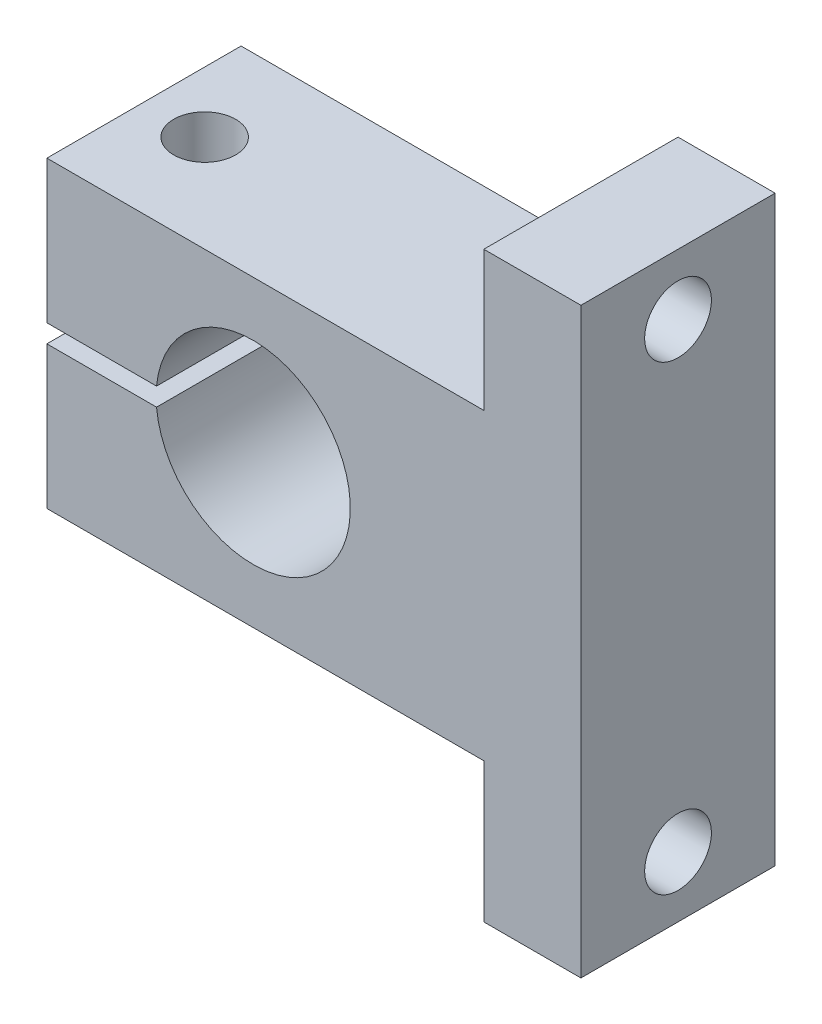
SolidWorks part; units mm, degrees
material "Liga 6061"
ref_plane "Plano frontal" through (0, 0, 0) normal (0, 0, 1) x (1, 0, 0)
ref_plane "Plano superior" through (0, 0, 0) normal (0, 1, 0) x (1, 0, 0)
ref_plane "Plano direito" through (0, 0, 0) normal (1, 0, 0) x (0, 0, -1)
sketch "Esboço1" plane through (0, 0, 0) normal (0, 0, 1) x (1, 0, 0)
  line L0 (0, 0) -> (0, 48)
  line L1 (0, 48) -> (-8, 48)
  line L2 (-8, 48) -> (-8, 36.5)
  line L3 (-8, 36.5) -> (-44, 36.5)
  line L4 (-44, 36.5) -> (-44, 24.75)
  line L5 (-44, 11.5) -> (-8, 11.5)
  line L6 (-8, 11.5) -> (-8, 0)
  line L7 (-8, 0) -> (0, 0)
  line L9 (-44, 24.75) -> (-34.9648, 24.75)
  line L11 (-44, 23.25) -> (-34.9648, 23.25)
  line L12 (-44, 23.25) -> (-44, 11.5)
  arc A0 (-34.9648, 23.25) -> (-34.9648, 24.75) centre (-27, 24) ccw
  dimension "D6" = 16
  dimension "D1" = 48
  dimension "D2" = 11.5
  dimension "D3" = 11.5
  dimension "D4" = 44
  dimension "D5" = 8
  dimension "D7" = 27
  dimension "D8" = 24
  dimension "D9" = 1.5
  dimension "D10" = 0.75
extrude "Extrusão1" add sketch "Esboço1" along normal blind 16
sketch "Esboço2" plane through (0, 36.5, 0) normal (0, 1, 0) x (1, 0, 0)
  line L0 (-44, -16) -> (-44, 0) construction
  line L1 (-34.9648, -16) -> (-44, -16) construction
  circle A0 centre (-39, -8) radius 2.55
  point P5 (-39.4824, -16)
  dimension "D1" = 5.1
  dimension "D2" = 5
  dimension "D3" = 8
extrude "Extrusão2" cut sketch "Esboço2" against normal up to next
hole_wizard "Furo roscado de M5x0.82" positions "3DSketch2" profile "Esboço4" tap size "M5x0.8" standard "Métrico Ansi"
sketch3d "3DSketch2"
  line L0 (-44, 23.25, 16) -> (-44, 23.25, 0) construction
  line L1 (-34.9648, 23.25, 0) -> (-44, 23.25, 0) construction
  point P0 (-39, 23.25, 8)
  dimension "D1" = 5
  dimension "D2" = 8
sketch "Esboço4" plane through (-39, 23.25, 8) normal (1, 0, 0) x (0, 0, 1)
  line L0 (0, 0) -> (0, 15.2618)
  line L1 (0, 15.2618) -> (2.1, 14)
  line L2 (2.1, 14) -> (2.1, 0)
  line L5 (2.1, 0) -> (0, 0)
  line L10 (0, 15.2618) -> (-2.1, 14) construction
  line L11 (0, -6.35) -> (0, 107.95) construction
  dimension "Tap Drill Dia." = 4.2
  dimension "Tap Drill Depth" = 14
  dimension "Drill Angle" = 118
cosmetic thread "Rosca de furo1" parameters "D1"=10, "D2"=5
sketch "Esboço5" plane through (-8, 0, 0) normal (-1, 0, 0) x (0, 0, 1)
  line L0 (16, 48) -> (0, 48) construction
  line L1 (0, 48) -> (0, 36.5) construction
  circle A0 centre (8, 43) radius 2.75
  circle A1 centre (8, 5) radius 2.75
  dimension "D1" = 5.5
  dimension "D2" = 5.5
  dimension "D3" = 5
  dimension "D5" = 5
  dimension "D6" = 8
extrude "Extrusão3" cut sketch "Esboço5" against normal through all
